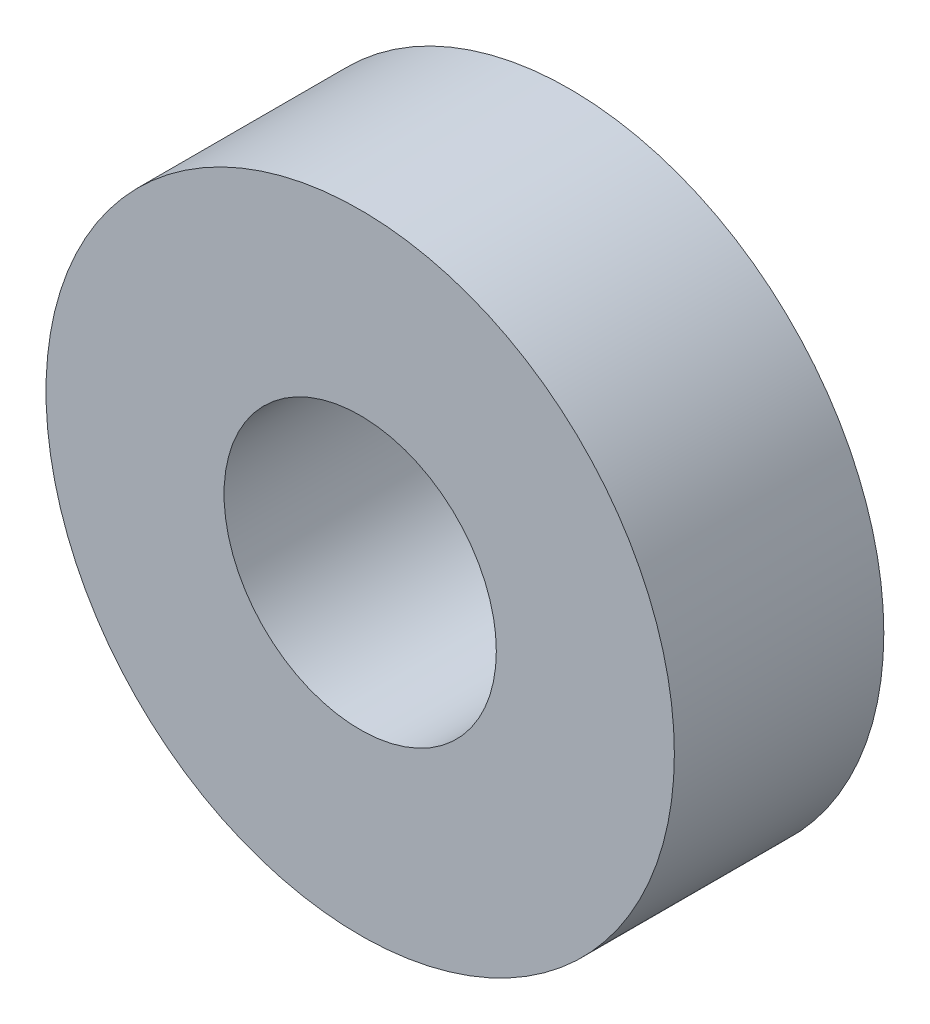
SolidWorks part; units mm, degrees
material "2014 Alloy"
ref_plane "Plan de face" through (0, 0, 0) normal (0, 0, 1) x (1, 0, 0)
ref_plane "Plan de dessus" through (0, 0, 0) normal (0, 1, 0) x (1, 0, 0)
ref_plane "Plan de droite" through (0, 0, 0) normal (1, 0, 0) x (0, 0, -1)
sketch "Sketch2" plane through (0, 0, 0) normal (0, 0, 1) x (1, 0, 0)
  circle A0 centre (0, 0) radius 3.25
  circle A1 centre (0, 0) radius 7.5
  dimension "D1" = 6.5
  dimension "D2" = 15
extrude "Boss-Extrude1" add sketch "Sketch2" along normal blind 5
